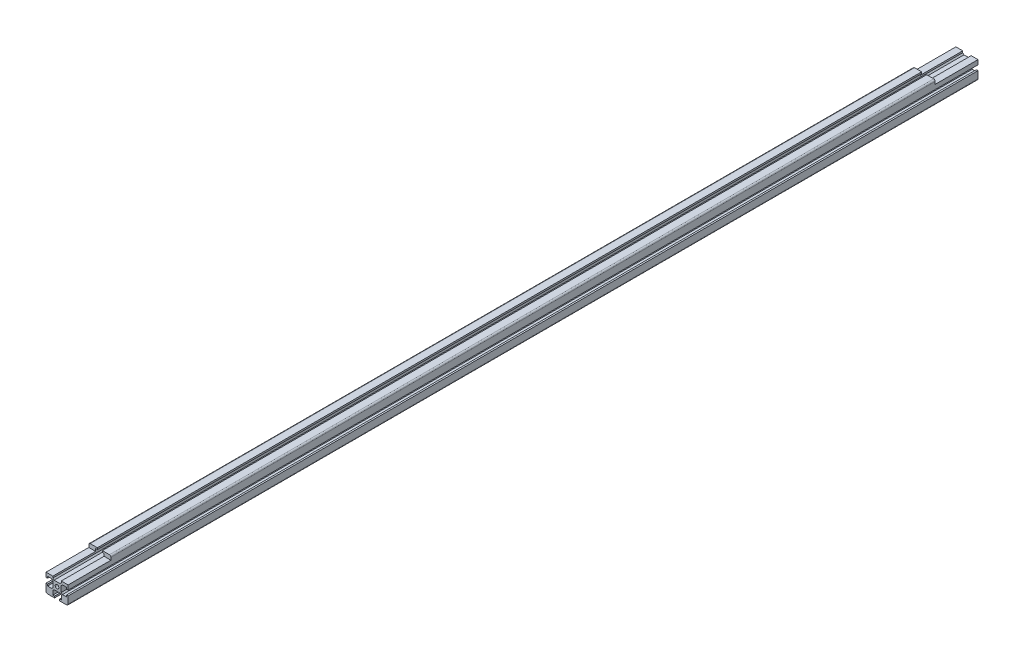
SolidWorks part; units mm, degrees
material "6061 Alloy"
ref_plane "Front Plane" through (0, 0, 0) normal (0, 0, 1) x (1, 0, 0)
ref_plane "Top Plane" through (0, 0, 0) normal (0, 1, 0) x (1, 0, 0)
ref_plane "Right Plane" through (0, 0, 0) normal (1, 0, 0) x (0, 0, -1)
sketch "Sketch1" plane through (0, 0, 0) normal (0, 0, 1) x (1, 0, 0)
  line L0 (0, 7.5) -> (0, -7.5) construction
  line L1 (7.5, 0) -> (-7.5, 0) construction
  line L2 (7.5, -7.5) -> (1.7, -7.5)
  line L3 (7.5, -7.5) -> (7.5, -1.7)
  line L4 (7.5, 7.5) -> (1.7, 7.5)
  line L5 (-7.5, -7.5) -> (-7.5, -1.7)
  line L6 (7.5, -7.5) -> (-7.5, 7.5) construction
  line L7 (7.5, 7.5) -> (-7.5, -7.5) construction
  line L8 (1.7, 7.5) -> (1.7, 6.4)
  line L9 (1.7, 6.4) -> (2.85, 6.4)
  line L10 (2.85, 6.4) -> (2.85, 3.6318)
  line L11 (2.85, 3.6318) -> (2.0182, 2.8)
  line L12 (2.0182, 2.8) -> (-2.0182, 2.8)
  line L13 (-2.85, 3.6318) -> (-2.0182, 2.8)
  line L14 (-2.85, 6.4) -> (-2.85, 3.6318)
  line L15 (-1.7, 6.4) -> (-2.85, 6.4)
  line L16 (-1.7, 7.5) -> (-1.7, 6.4)
  line L17 (6.4, -1.7) -> (6.4, -2.85)
  line L18 (7.5, -1.7) -> (6.4, -1.7)
  line L19 (6.4, -2.85) -> (3.6318, -2.85)
  line L20 (3.6318, -2.85) -> (2.8, -2.0182)
  line L21 (2.8, -2.0182) -> (2.8, 2.0182)
  line L22 (3.6318, 2.85) -> (2.8, 2.0182)
  line L23 (6.4, 2.85) -> (3.6318, 2.85)
  line L24 (6.4, 1.7) -> (6.4, 2.85)
  line L25 (7.5, 1.7) -> (6.4, 1.7)
  line L26 (-1.7, -6.4) -> (-2.85, -6.4)
  line L27 (-1.7, -7.5) -> (-1.7, -6.4)
  line L28 (-2.85, -6.4) -> (-2.85, -3.6318)
  line L29 (-2.85, -3.6318) -> (-2.0182, -2.8)
  line L30 (-2.0182, -2.8) -> (2.0182, -2.8)
  line L31 (2.85, -3.6318) -> (2.0182, -2.8)
  line L32 (2.85, -6.4) -> (2.85, -3.6318)
  line L33 (1.7, -6.4) -> (2.85, -6.4)
  line L34 (1.7, -7.5) -> (1.7, -6.4)
  line L35 (-6.4, 1.7) -> (-6.4, 2.85)
  line L36 (-7.5, 1.7) -> (-6.4, 1.7)
  line L37 (-6.4, 2.85) -> (-3.6318, 2.85)
  line L38 (-3.6318, 2.85) -> (-2.8, 2.0182)
  line L39 (-2.8, 2.0182) -> (-2.8, -2.0182)
  line L40 (-3.6318, -2.85) -> (-2.8, -2.0182)
  line L41 (-6.4, -2.85) -> (-3.6318, -2.85)
  line L42 (-6.4, -1.7) -> (-6.4, -2.85)
  line L43 (-7.5, -1.7) -> (-6.4, -1.7)
  line L44 (-1.7, 7.5) -> (-7.5, 7.5)
  line L45 (-7.5, 1.7) -> (-7.5, 7.5)
  line L46 (-1.7, -7.5) -> (-7.5, -7.5)
  line L47 (7.5, 1.7) -> (7.5, 7.5)
  circle A0 centre (0, 0) radius 1.25
  point P3 (0, 0)
  point P19 (0, 2.8)
  point P56 (0, 0)
  dimension "D3" = 2.5
  dimension "D2" = 15
  dimension "D4" = 1.1
  dimension "D5" = 3.6
  dimension "D6" = 5.7
  dimension "D7" = 3.4
  dimension "D8" = 4
extrude "Boss-Extrude1" add sketch "Sketch1" along normal blind 616.81
fillet "Fillet1" radius 1 4 edges at (7.5, -7.5, 308.405) (-7.5, -7.5, 308.405) (7.5, 7.5, 308.405) (-7.5, 7.5, 308.405)
sketch "Sketch2" plane through (0, 7.5, 0) normal (0, 1, 0) x (1, 0, 0)
  line L0 (7.5, 0) -> (7.5, -616.81) construction
  line L1 (-7.5, -616.81) -> (7.5, -616.81)
  line L2 (-7.5, -616.81) -> (-7.5, -587.8)
  line L3 (-7.5, -587.8) -> (7.5, -587.8)
  line L4 (7.5, -616.81) -> (7.5, -587.8)
  dimension "D1" = 29.01
extrude "Cut-Extrude2" cut sketch "Sketch2" against normal blind 2.74
sketch "Sketch3" plane through (0, 7.5, 0) normal (0, 1, 0) x (1, 0, 0)
  line L0 (7.5, 0) -> (7.5, -587.8) construction
  line L1 (-7.5, 0) -> (7.5, 0)
  line L2 (-7.5, 0) -> (-7.5, -29.01)
  line L3 (-7.5, -29.01) -> (7.5, -29.01)
  line L4 (7.5, 0) -> (7.5, -29.01)
  dimension "D1" = 29.01
extrude "Cut-Extrude3" cut sketch "Sketch3" against normal blind 2.74
